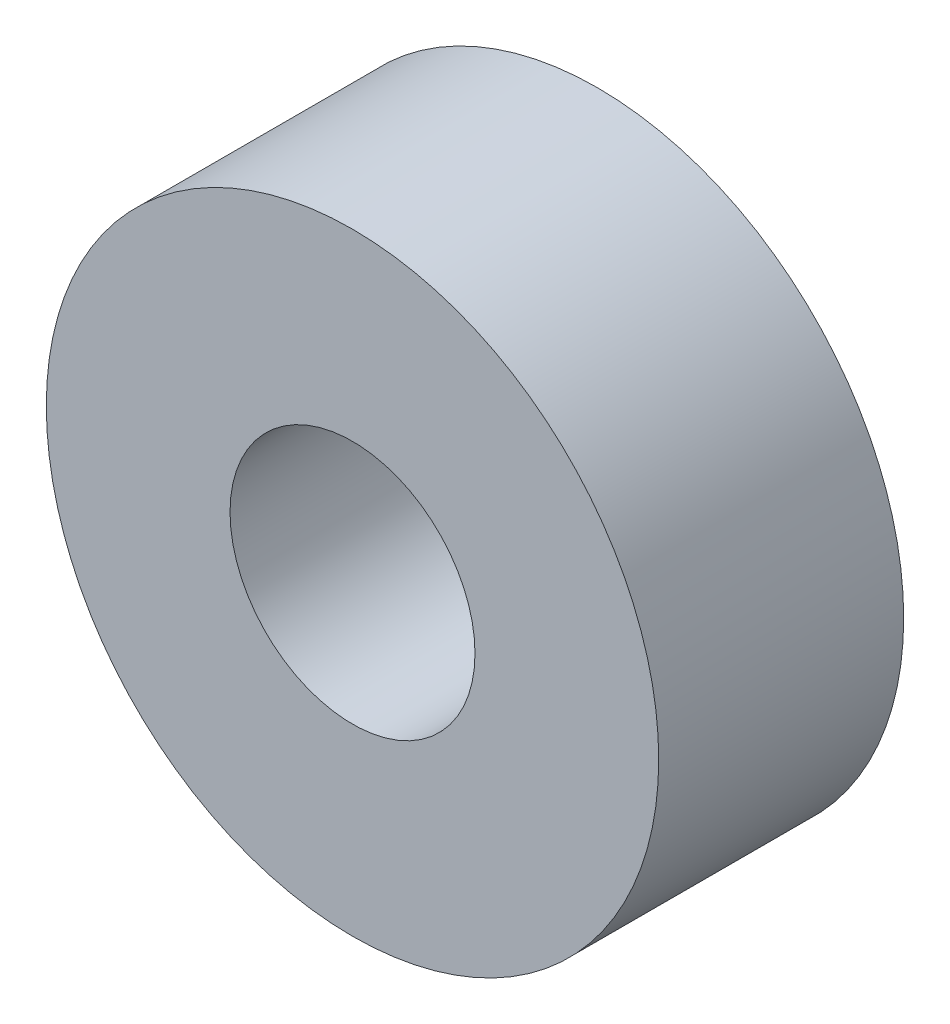
SolidWorks part; units mm, degrees
ref_plane "Front Plane" through (0, 0, 0) normal (0, 0, 1) x (1, 0, 0)
ref_plane "Top Plane" through (0, 0, 0) normal (0, 1, 0) x (1, 0, 0)
ref_plane "Right Plane" through (0, 0, 0) normal (1, 0, 0) x (0, 0, -1)
sketch "Sketch1" plane through (0, 0, 0) normal (0, 0, 1) x (1, 0, 0)
  circle A1 centre (0, 0) radius 1
extrude "Extrude-Thin1" add sketch "Sketch1" along normal blind 2 thin
